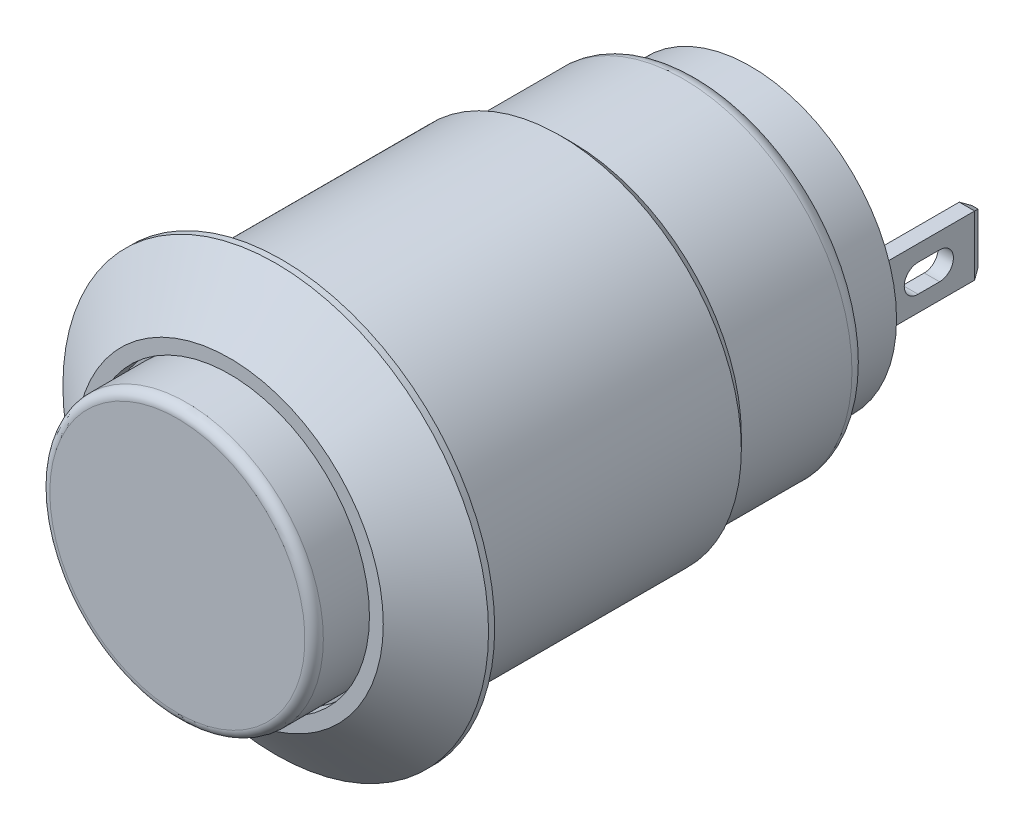
SolidWorks part; units mm, degrees
ref_plane "Front Plane" through (0, 0, 0) normal (0, 0, 1) x (1, 0, 0)
ref_plane "Top Plane" through (0, 0, 0) normal (0, 1, 0) x (1, 0, 0)
ref_plane "Right Plane" through (0, 0, 0) normal (1, 0, 0) x (0, 0, -1)
sketch "Sketch8" plane through (0, 0, 0) normal (1, 0, 0) x (0, 0, -1)
  line L0 (0, 0) -> (24.2591, 0) construction
  line L1 (0, 0) -> (0, 4.45)
  line L2 (0, 4.45) -> (2.2, 4.45)
  line L3 (2.2, 4.45) -> (2.2, 4.55)
  line L4 (2.2, 4.55) -> (1.7, 4.55)
  line L5 (1.7, 4.55) -> (1.7, 5)
  line L6 (1.7, 5) -> (3.2, 6.925)
  line L7 (3.2, 6.925) -> (3.4, 6.925)
  line L8 (3.4, 6.925) -> (3.4, 5.9)
  line L9 (3.4, 5.9) -> (12.45, 5.9)
  line L10 (12.45, 5.9) -> (12.85, 5.5)
  line L11 (12.85, 5.5) -> (16.95, 5.5)
  line L12 (16.95, 5.5) -> (16.95, 4.75)
  line L13 (16.95, 4.75) -> (18.65, 4.75)
  line L14 (18.65, 4.75) -> (18.65, 0)
  line L15 (18.65, 0) -> (0, 0)
  point P15 (1.95, 4.55)
  dimension "D1" = 8.9
  dimension "D2" = 9.1
  dimension "D3" = 10
  dimension "D4" = 13.85
  dimension "D5" = 1.7
  dimension "D6" = 0.5
  dimension "D7" = 1.7
  dimension "D8" = 0.2
  dimension "D9" = 11.8
  dimension "D10" = 11
  dimension "D11" = 9.5
  dimension "D12" = 1.7
  dimension "D13" = 15.25
  dimension "D14" = 9.45
  dimension "D15" = 45
revolve "Revolve1" add sketch "Sketch8" angle 360 about L0
fillet "Fillet2" radius 0.5 1 edges at (5.5, 0, -16.95)
fillet "Fillet3" radius 0.3 1 edges at (4.45, 0, 0)
sketch "Sketch9" plane through (0, 0, -18.65) normal (0, 0, -1) x (-1, 0, 0)
  line L0 (0, 0) -> (0, -3.4001) construction
  line L1 (-3.95, -0.975) -> (-3.45, -0.975)
  line L2 (-3.95, -0.975) -> (-3.95, 0.975)
  line L3 (-3.95, 0.975) -> (-3.45, 0.975)
  line L4 (-3.45, -0.975) -> (-3.45, 0.975)
  line L5 (-3.95, -0.975) -> (-3.45, 0.975) construction
  line L6 (-3.95, 0.975) -> (-3.45, -0.975) construction
  line L7 (3.45, -0.975) -> (3.95, -0.975)
  line L8 (3.45, -0.975) -> (3.45, 0.975)
  line L9 (3.45, 0.975) -> (3.95, 0.975)
  line L10 (3.95, -0.975) -> (3.95, 0.975)
  line L11 (3.45, -0.975) -> (3.95, 0.975) construction
  line L12 (3.45, 0.975) -> (3.95, -0.975) construction
  point P0 (-3.7, 0)
  point P5 (3.7, 0)
  dimension "D1" = 0.5
  dimension "D2" = 6.9
  dimension "D3" = 1.95
extrude "Boss-Extrude5" add sketch "Sketch9" along normal blind 3.6
chamfer "Chamfer2" distance 0.15 angle 60 8 edges at (-3.7, -0.975, -22.25) (-3.45, 0, -22.25) (-3.7, 0.975, -22.25) (-3.95, 0, -22.25) (3.7, -0.975, -22.25) (3.95, 0, -22.25) (3.7, 0.975, -22.25) (3.45, 0, -22.25)
sketch "Sketch10" plane through (0, 0, 0) normal (1, 0, 0) x (0, 0, -1)
  line L0 (20.15, 0) -> (20.85, 0) construction
  line L1 (20.15, 0.45) -> (20.85, 0.45)
  line L2 (20.15, -0.45) -> (20.85, -0.45)
  line L3 (18.65, -4.75) -> (18.65, 4.75) construction
  arc A0 (20.15, 0.45) -> (20.15, -0.45) centre (20.15, 0) ccw
  arc A1 (20.85, -0.45) -> (20.85, 0.45) centre (20.85, 0) ccw
  point P2 (20.5, 0)
  dimension "D1" = 1.6
  dimension "D2" = 1.5
  dimension "D3" = 0.9
extrude "Cut-Extrude2" cut sketch "Sketch10" against normal through all both and the other way through all
